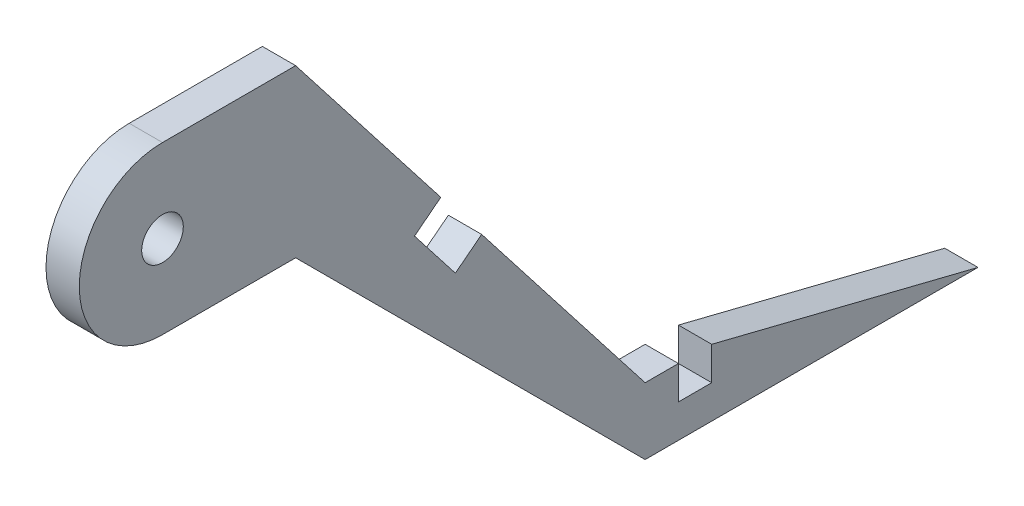
SolidWorks part; units mm, degrees
material "1023 Carbon Steel Sheet (SS)"
ref_plane "Front Plane" through (0, 0, 0) normal (0, 0, 1) x (1, 0, 0)
ref_plane "Top Plane" through (0, 0, 0) normal (0, 1, 0) x (1, 0, 0)
ref_plane "Right Plane" through (0, 0, 0) normal (1, 0, 0) x (0, 0, -1)
sketch "Sketch1" plane through (0, 0, 0) normal (1, 0, 0) x (0, 0, -1)
  line L1 (0, 31.75) -> (50.8, 31.75)
  line L2 (0, -31.75) -> (50.8, -31.75)
  line L4 (50.8, -31.75) -> (184.15, -165.1)
  line L6 (184.15, -139.7) -> (50.8, 31.75)
  line L11 (184.15, -165.1) -> (311.15, -165.1)
  line L12 (311.15, -165.1) -> (209.55, -139.7)
  line L13 (209.55, -139.7) -> (209.55, -152.4)
  line L14 (209.55, -152.4) -> (196.85, -152.4)
  line L15 (196.85, -152.4) -> (196.85, -139.7)
  line L16 (196.85, -139.7) -> (184.15, -139.7)
  arc A0 (0, 31.75) -> (0, -31.75) centre (0, 0) ccw
  dimension "D1" = 63.5
  dimension "D2" = 50.8
  dimension "D3" = 135
  dimension "D4" = 25.4
  dimension "D5" = 133.35
  dimension "D6" = 12.7
  dimension "D7" = 12.7
  dimension "D8" = 127
extrude "main" add sketch "Sketch1" along normal blind 12.7
sketch "Sketch2" plane through (12.7, 0, 0) normal (1, 0, 0) x (0, 0, -1)
  circle A0 centre (0, 0) radius 7.9375
  dimension "D1" = 15.875
extrude "axle" cut sketch "Sketch2" against normal up to surface (12.7 mm away) up to face at (0, -95.8273, -142.0091)
sketch "Sketch5" plane through (0, 36.5858, -47.0388) normal (0, 0.6139, -0.7894) x (-1, 0, 0)
  line L0 (-12.7, -223.3297) -> (-12.7, -6.1263) construction
  line L1 (-12.7, -96.3297) -> (0, -96.3297)
  line L2 (-12.7, -96.3297) -> (-12.7, -121.7297)
  line L3 (-12.7, -121.7297) -> (0, -121.7297)
  line L4 (0, -96.3297) -> (0, -121.7297)
  line L5 (0, -223.3297) -> (0, -6.1263) construction
  line L6 (-12.7, -223.3297) -> (0, -223.3297) construction
  point P8 (-6.35, -121.7297)
  dimension "D1" = 25.4
  dimension "D2" = 101.6
extrude "barwide" cut sketch "Sketch5" against normal blind 12.7
